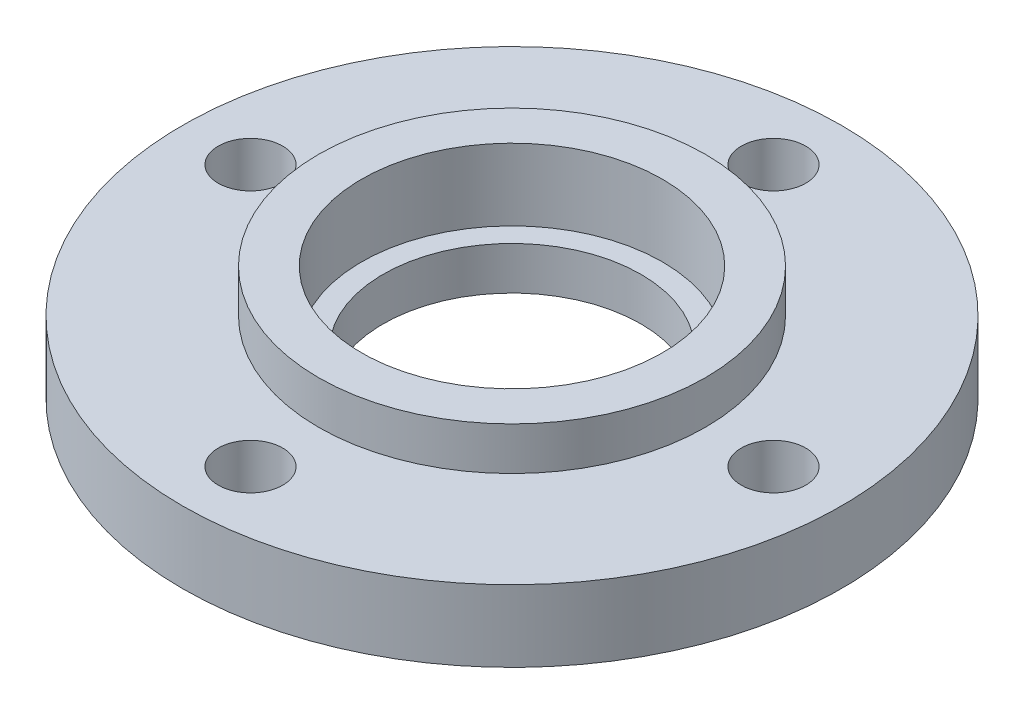
SolidWorks part; units mm, degrees
ref_plane "Front Plane" through (0, 0, 0) normal (0, 0, 1) x (1, 0, 0)
ref_plane "Top Plane" through (0, 0, 0) normal (0, 1, 0) x (1, 0, 0)
ref_plane "Right Plane" through (0, 0, 0) normal (1, 0, 0) x (0, 0, -1)
ref_axis "Axis1" through (0, -55, 0) along (0, 1, 0)
sketch "Sketch1" plane through (0, 0, 0) normal (0, 0, 1) x (1, 0, 0)
  line L0 (9, 0) -> (9, -3)
  line L1 (9, -3) -> (23, -3)
  line L2 (23, -3) -> (23, 2)
  line L3 (23, 2) -> (13.5, 2)
  line L4 (13.5, 2) -> (13.5, 5)
  line L5 (13.5, 5) -> (10.5, 5)
  line L6 (10.5, 5) -> (10.5, 0)
  line L7 (10.5, 0) -> (9, 0)
  line L8 (0, -55) -> (0, 55) construction
  dimension "D1" = 9
  dimension "D2" = 5
  dimension "D3" = 10.5
  dimension "D4" = 3
  dimension "D5" = 23
  dimension "D6" = 3
  dimension "D7" = 3
  dimension "D8" = 5
revolve "Revolve1" add sketch "Sketch1" angle 360 about axis through (0, -55, 0) along (0, 1, 0)
hole_wizard "M4 Clearance Hole1" positions "Sketch2" profile "Sketch3" hole size "M4" standard "ISO" end condition through all
sketch "Sketch2" plane through (0, 2, 0) normal (0, 1, 0) x (1, 0, 0)
  point P0 (18.25, 0)
  dimension "D1" = 18.25
sketch "Sketch3" plane through (18.25, 2, 0) normal (1, 0, 0) x (0, 0, 1)
  line L0 (0, 0) -> (0, 5)
  line L1 (0, 5) -> (2.25, 5)
  line L2 (2.25, 5) -> (2.25, 0)
  line L5 (2.25, 0) -> (0, 0)
  line L11 (0, -6.35) -> (0, 107.95) construction
  dimension "Thru Hole Dia." = 4.5
  dimension "Thru Hole Depth" = 5
pattern_circular "CirPattern1" count 4 every 90 about axis through (0, 0, 0) along (0, 1, 0) of "M4 Clearance Hole1"
